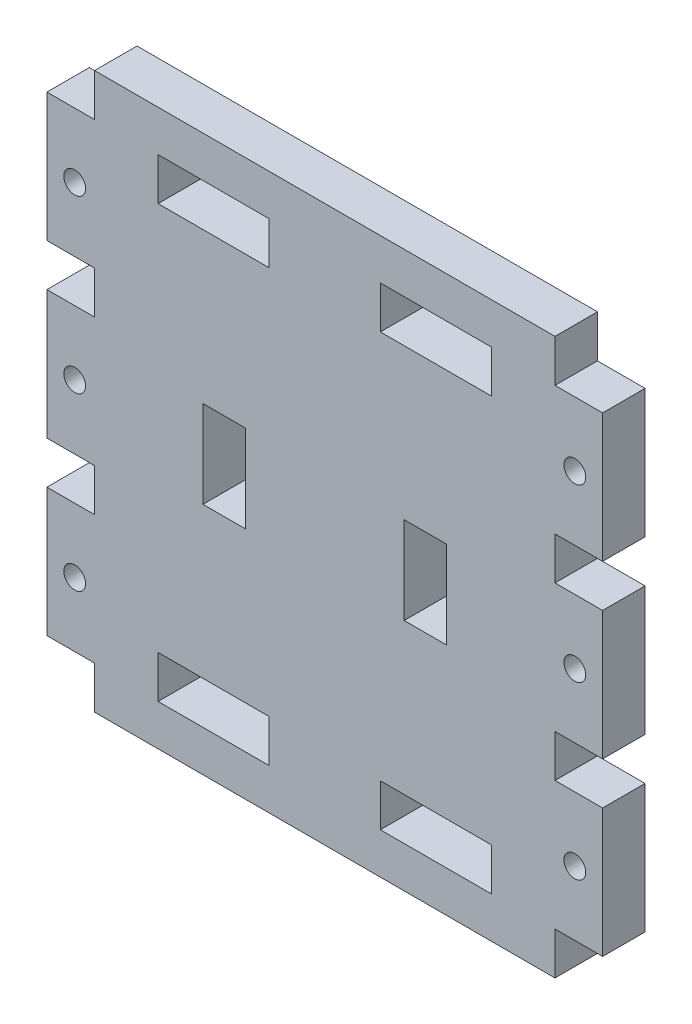
SolidWorks part; units mm, degrees
ref_plane "Front Plane" through (0, 0, 0) normal (0, 0, 1) x (1, 0, 0)
ref_plane "Top Plane" through (0, 0, 0) normal (0, 1, 0) x (1, 0, 0)
ref_plane "Right Plane" through (0, 0, 0) normal (1, 0, 0) x (0, 0, -1)
sketch "Model" plane through (0, 0, 0) normal (0, 0, 1) x (1, 0, 0)
  line L188 (6, 5.35) -> (6, 0)
  line L189 (0, 5.35) -> (6, 5.35)
  line L190 (6, 21.55) -> (0, 21.55)
  line L191 (6, 26.9) -> (6, 21.55)
  line L192 (0, 26.9) -> (6, 26.9)
  line L193 (6, 43.1) -> (0, 43.1)
  line L194 (6, 48.45) -> (6, 43.1)
  line L195 (0, 48.45) -> (6, 48.45)
  line L196 (0, 64.65) -> (0, 48.45)
  line L197 (6, 64.65) -> (0, 64.65)
  line L198 (6, 70) -> (6, 64.65)
  line L199 (64, 70) -> (6, 70)
  line L200 (64, 64.65) -> (64, 70)
  line L201 (70, 64.65) -> (64, 64.65)
  line L202 (70, 48.45) -> (70, 64.65)
  line L203 (64, 48.45) -> (70, 48.45)
  line L204 (64, 43.1) -> (64, 48.45)
  line L205 (70, 43.1) -> (64, 43.1)
  line L206 (64, 26.9) -> (70, 26.9)
  line L207 (64, 21.55) -> (64, 26.9)
  line L208 (70, 21.55) -> (64, 21.55)
  line L209 (64, 5.35) -> (70, 5.35)
  line L210 (64, 0) -> (64, 5.35)
  line L211 (6, 0) -> (64, 0)
  line L212 (19.65, 29.5) -> (25, 29.5)
  line L213 (25, 29.5) -> (25, 40.5)
  line L214 (25, 40.5) -> (19.65, 40.5)
  line L215 (19.65, 40.5) -> (19.65, 29.5)
  line L216 (45, 29.5) -> (50.35, 29.5)
  line L217 (50.35, 29.5) -> (50.35, 40.5)
  line L218 (50.35, 40.5) -> (45, 40.5)
  line L219 (45, 40.5) -> (45, 29.5)
  line L220 (56, 5.17) -> (56, 10.52)
  line L221 (56, 10.52) -> (42, 10.52)
  line L222 (42, 10.52) -> (42, 5.17)
  line L223 (42, 5.17) -> (56, 5.17)
  line L224 (28, 5.17) -> (28, 10.52)
  line L225 (28, 10.52) -> (14, 10.52)
  line L226 (14, 10.52) -> (14, 5.17)
  line L227 (14, 5.17) -> (28, 5.17)
  line L228 (56, 59.48) -> (56, 64.83)
  line L229 (56, 64.83) -> (42, 64.83)
  line L230 (42, 64.83) -> (42, 59.48)
  line L231 (42, 59.48) -> (56, 59.48)
  line L232 (28, 59.48) -> (28, 64.83)
  line L233 (28, 64.83) -> (14, 64.83)
  line L234 (14, 64.83) -> (14, 59.48)
  line L235 (14, 59.48) -> (28, 59.48)
  line L236 (70, 26.9) -> (70, 43.1)
  line L237 (0, 43.1) -> (0, 26.9)
  line L238 (0, 21.55) -> (0, 5.35)
  line L239 (70, 5.35) -> (70, 21.55)
  circle A0 centre (3.5, 35) radius 1.375
  circle A1 centre (3.5, 56.55) radius 1.375
  circle A2 centre (3.5, 13.45) radius 1.375
  circle A3 centre (66.5, 13.45) radius 1.375
  circle A4 centre (66.5, 56.55) radius 1.375
  circle A5 centre (66.5, 35) radius 1.375
extrude "Boss-Extrude1" add sketch "Model" along normal blind 5.35
